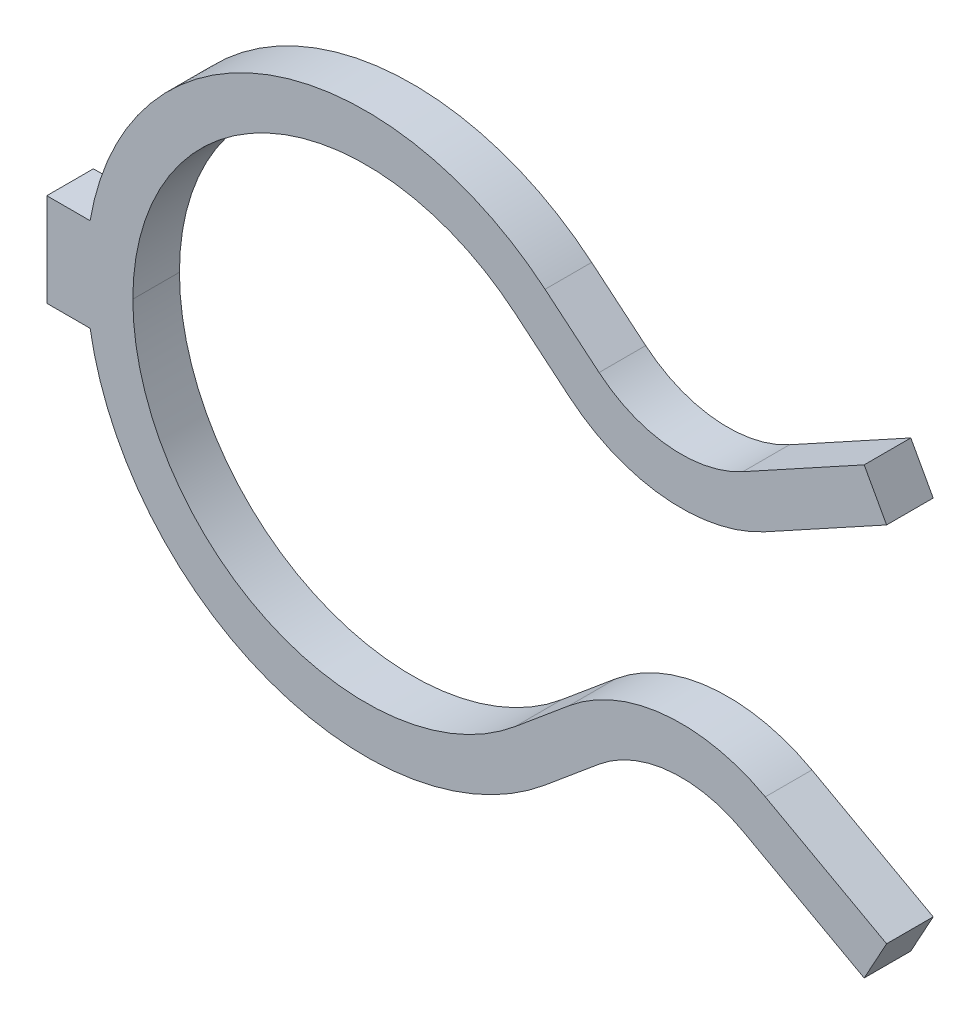
SolidWorks part; units mm, degrees
ref_plane "Front Plane" through (0, 0, 0) normal (0, 0, 1) x (1, 0, 0)
ref_plane "Top Plane" through (0, 0, 0) normal (0, 1, 0) x (1, 0, 0)
ref_plane "Right Plane" through (0, 0, 0) normal (1, 0, 0) x (0, 0, -1)
other "Configuration Table"
sketch "Sketch1" plane through (0, 0, 0) normal (0, 0, 1) x (1, 0, 0)
  line L0 (-80.2056, 0) -> (84.4493, 0) construction
  line L1 (16.2772, 19.4991) -> (22.1629, 14.5859)
  line L2 (19.5326, 23.3989) -> (25.4183, 18.4857)
  line L3 (43.536, 12.5098) -> (56.7574, 19.7657)
  line L4 (41.0919, 16.9632) -> (54.3134, 24.2192)
  line L5 (19.5326, -23.3989) -> (25.4183, -18.4857)
  line L6 (56.7574, 19.7657) -> (54.3134, 24.2192)
  line L7 (56.7574, -19.7657) -> (54.3134, -24.2192)
  line L9 (41.0919, -16.9632) -> (54.3134, -24.2192)
  line L10 (43.536, -12.5098) -> (56.7574, -19.7657)
  line L12 (16.2772, -19.4991) -> (22.1629, -14.5859)
  line L13 (-30.0537, 5.08) -> (-34.7768, 5.08)
  line L14 (-34.7768, 5.08) -> (-34.7768, -5.08)
  line L15 (-30.0537, -5.08) -> (-34.7768, -5.08)
  arc A0 (16.2772, 19.4991) -> (16.2772, -19.4991) centre (0, 0) ccw
  arc A2 (22.1629, 14.5859) -> (43.536, 12.5098) centre (34.3708, 29.2102) ccw
  arc A3 (25.4183, -18.4857) -> (41.0919, -16.9632) centre (34.3708, -29.2102) cw
  arc A5 (25.4183, 18.4857) -> (41.0919, 16.9632) centre (34.3708, 29.2102) ccw
  arc A6 (19.5326, 23.3989) -> (-30.0537, 5.08) centre (0, 0) ccw
  arc A7 (22.1629, -14.5859) -> (43.536, -12.5098) centre (34.3708, -29.2102) cw
  arc A10 (-30.0537, -5.08) -> (19.5326, -23.3989) centre (0, 0) ccw
  point P30 (-34.7768, 0)
  dimension "D3" = 29.2102
  dimension "D6" = 5.08
  dimension "D2" = 7.6669
  dimension "D4" = 15.0817
  dimension "D7" = 4.7231
  dimension "D5" = 5.08
extrude "Extrude1" add sketch "Sketch1" along normal blind 5.08
split line "Split Line1"
